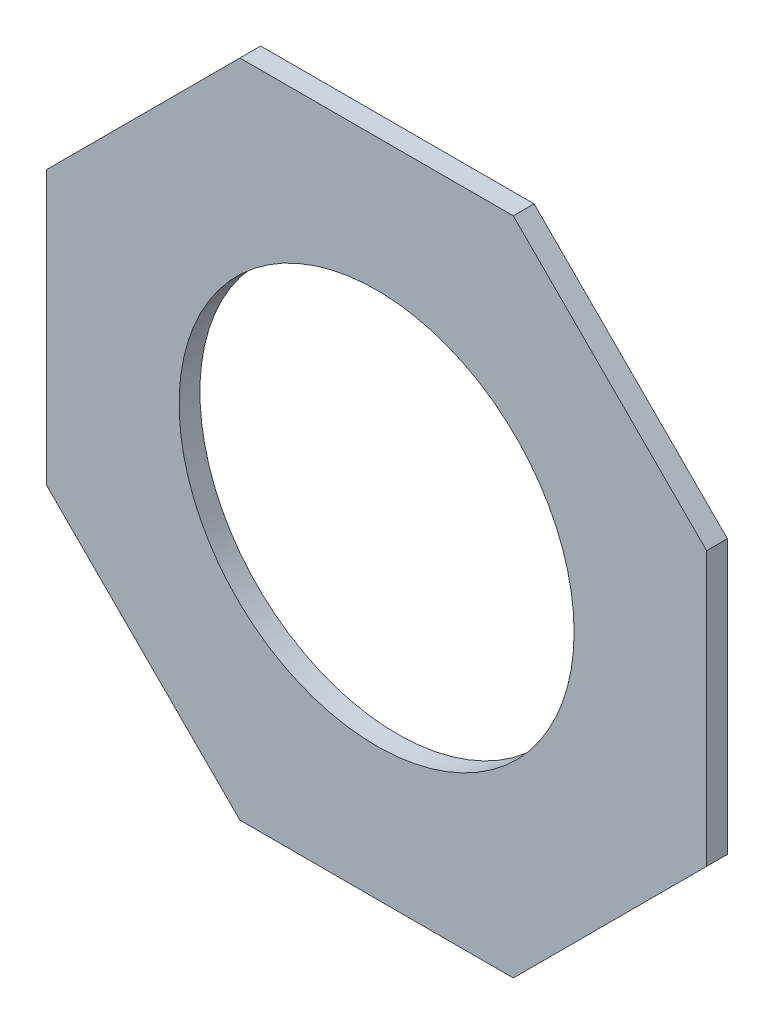
SolidWorks part; units mm, degrees
ref_plane "Front Plane" through (0, 0, 0) normal (0, 0, 1) x (1, 0, 0)
ref_plane "Top Plane" through (0, 0, 0) normal (0, 1, 0) x (1, 0, 0)
ref_plane "Right Plane" through (0, 0, 0) normal (1, 0, 0) x (0, 0, -1)
sketch "Sketch1" plane through (0, 0, 0) normal (0, 0, 1) x (1, 0, 0)
  line L1 (6.5756, 15.875) -> (-6.5756, 15.875)
  line L2 (-6.5756, 15.875) -> (-15.875, 6.5756)
  line L3 (-15.875, 6.5756) -> (-15.875, -6.5756)
  line L4 (-15.875, -6.5756) -> (-6.5756, -15.875)
  line L5 (-6.5756, -15.875) -> (6.5756, -15.875)
  line L6 (6.5756, -15.875) -> (15.875, -6.5756)
  line L7 (15.875, -6.5756) -> (15.875, 6.5756)
  line L8 (15.875, 6.5756) -> (6.5756, 15.875)
  circle A0 centre (0, 0) radius 15.875 construction
  circle A1 centre (0, 0) radius 9.5
  dimension "D2" = 19
  dimension "D1" = 31.75
extrude "Boss-Extrude1" add sketch "Sketch1" along normal blind 1
